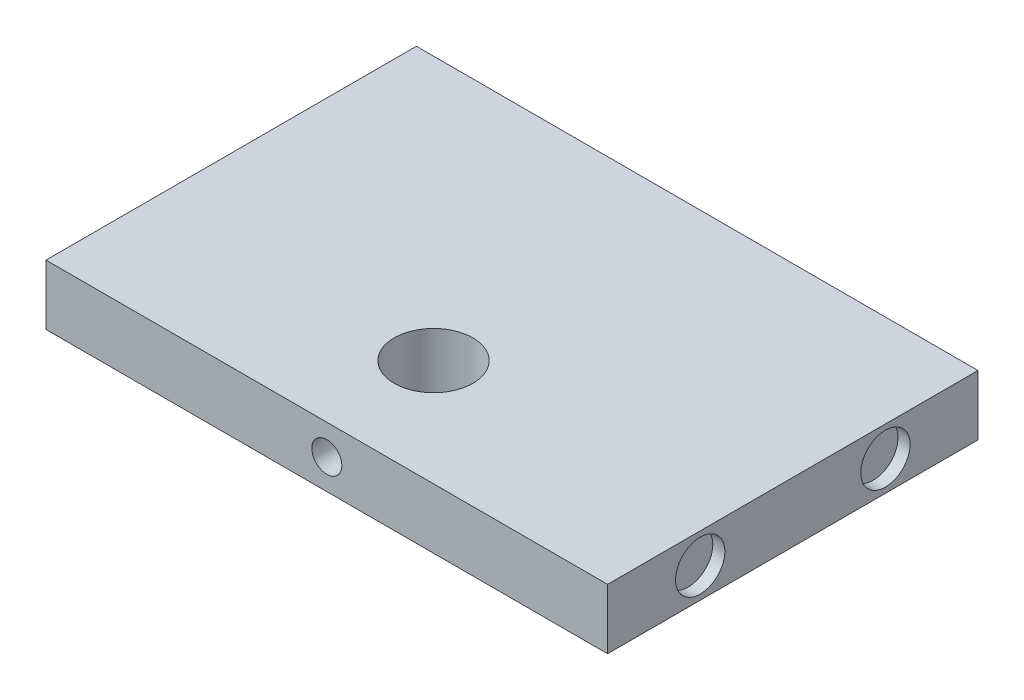
SolidWorks part; units mm, degrees
ref_plane "Front Plane" through (0, 0, 0) normal (0, 0, 1) x (1, 0, 0)
ref_plane "Top Plane" through (0, 0, 0) normal (0, 1, 0) x (1, 0, 0)
ref_plane "Right Plane" through (0, 0, 0) normal (1, 0, 0) x (0, 0, -1)
sketch "Croquis1" plane through (0, 0, 0) normal (0, 1, 0) x (1, 0, 0)
  line L0 (0, 30.8) -> (0, -6.5) construction
  line L1 (46.7, -30.8) -> (-46.7, -30.8)
  line L2 (46.7, -30.8) -> (46.7, 30.8)
  line L3 (46.7, 30.8) -> (-46.7, 30.8)
  line L4 (-46.7, -30.8) -> (-46.7, 30.8)
  line L5 (46.7, -30.8) -> (-46.7, 30.8) construction
  line L6 (46.7, 30.8) -> (-46.7, -30.8) construction
  circle A0 centre (0, -13.05) radius 6.55
  point P0 (0, 0)
  dimension "D3" = 13.1
  dimension "D1" = 93.4
  dimension "D2" = 61.6
extrude "Saliente-Extruir1" add sketch "Croquis1" along normal blind 10
sketch "Croquis2" plane through (-46.7, 0, 0) normal (-1, 0, 0) x (0, 0, 1)
  line L0 (0, 10) -> (0, 0) construction
  line L1 (-30.8, 10) -> (30.8, 10) construction
  line L2 (-30.8, 0) -> (30.8, 0) construction
  line L3 (-30.8, 5) -> (0, 5) construction
  line L4 (-30.8, 10) -> (-30.8, 0) construction
  circle A0 centre (-15.4, 5) radius 4.1
  circle A1 centre (15.4, 5) radius 4.1
extrude "Cortar-Extruir1" cut sketch "Croquis2" against normal blind 2
mirror "Simetría2" about plane through (0, 0, 0) normal (1, 0, 0) of "Cortar-Extruir1"
sketch "Croquis3" plane through (0, 0, 30.8) normal (0, 0, 1) x (1, 0, 0)
  line L0 (0, 10) -> (0, 0) construction
  line L1 (-46.7, 10) -> (46.7, 10) construction
  line L2 (-46.7, 0) -> (46.7, 0) construction
  circle A0 centre (0, 5) radius 2.5
  dimension "D1" = 5
extrude "Cortar-Extruir2" cut sketch "Croquis3" against normal up to next
